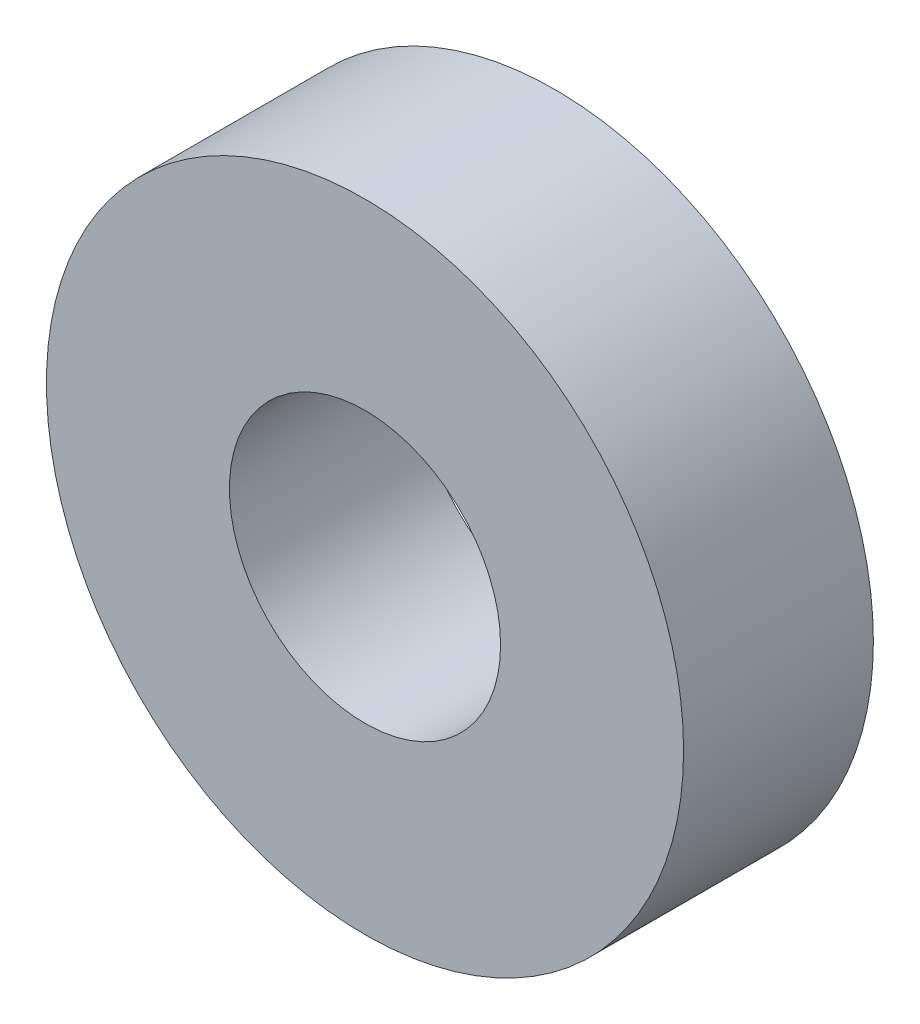
SolidWorks part; units mm, degrees
material "Plain Carbon Steel"
ref_plane "Front Plane" through (0, 0, 0) normal (0, 0, 1) x (1, 0, 0)
ref_plane "Top Plane" through (0, 0, 0) normal (0, 1, 0) x (1, 0, 0)
ref_plane "Right Plane" through (0, 0, 0) normal (1, 0, 0) x (0, 0, -1)
sketch "Sketch2" plane through (0, 0, 0) normal (0, 0, 1) x (1, 0, 0)
  circle A0 centre (0, 0) radius 10
  circle A1 centre (0, 0) radius 23.5
  dimension "D1" = 20
  dimension "D2" = 47
extrude "Boss-Extrude1" add sketch "Sketch2" along normal blind 14
